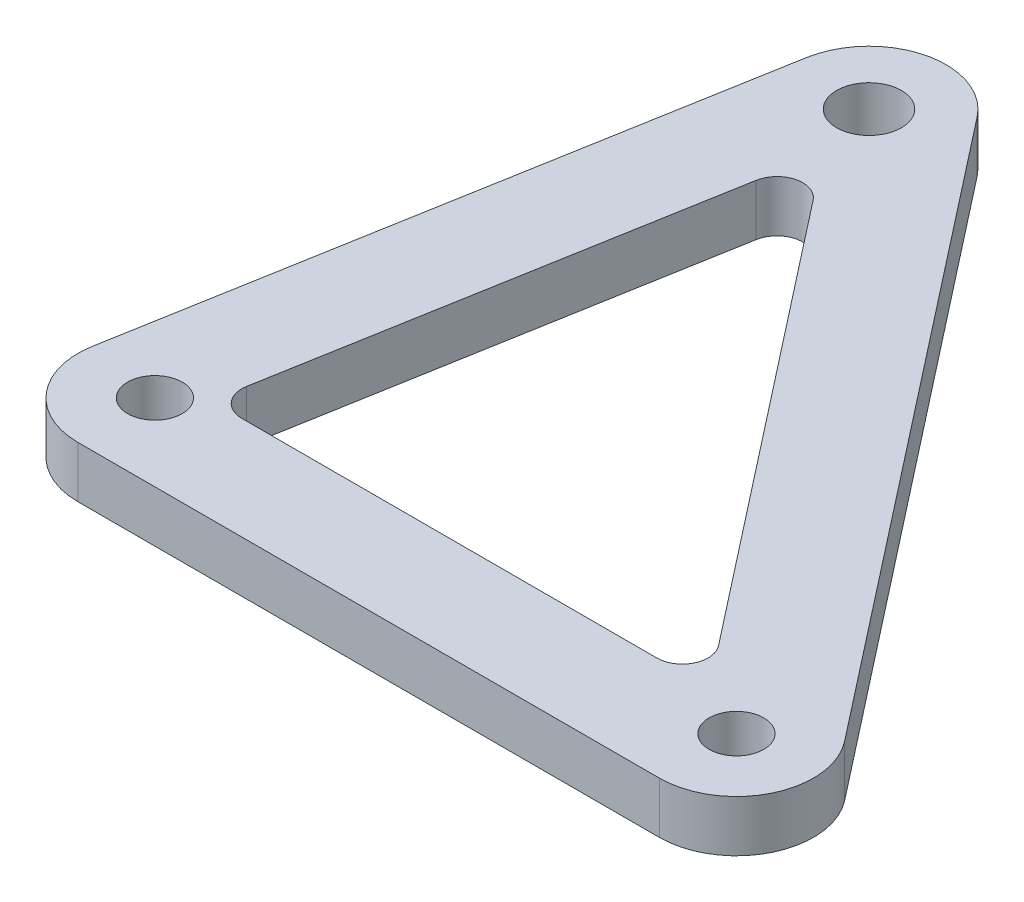
SolidWorks part; units mm, degrees
ref_plane "Front Plane" through (0, 0, 0) normal (0, 0, 1) x (1, 0, 0)
ref_plane "Top Plane" through (0, 0, 0) normal (0, 1, 0) x (1, 0, 0)
ref_plane "Right Plane" through (0, 0, 0) normal (1, 0, 0) x (0, 0, -1)
sketch "Sketch1" plane through (0, 0, 0) normal (0, 1, 0) x (1, 0, 0)
  line L0 (0, 0) -> (71.882, 0) construction
  line L1 (71.882, 0) -> (13.2224, 75.044) construction
  line L2 (13.2224, 75.044) -> (0, 0) construction
  line L3 (6.3163, 90.7407) -> (-10.6935, -5.7991)
  line L4 (-7.5666, -9.525) -> (84.9054, -9.525)
  line L5 (87.4068, -4.3947) -> (11.9446, 92.1451)
  line L6 (19.503, 61.8536) -> (61.3601, 8.3053)
  line L7 (58.8586, 3.175) -> (7.5666, 3.175)
  line L8 (4.4398, 6.9009) -> (13.8747, 60.4492)
  circle A0 centre (0, 0) radius 3.3782
  circle A1 centre (13.2224, 75.044) radius 4
  circle A2 centre (71.882, 0) radius 3.3782
  arc A3 (61.3601, 8.3053) -> (58.8586, 3.175) centre (58.8586, 6.35) cw
  arc A4 (7.5666, 3.175) -> (4.4398, 6.9009) centre (7.5666, 6.35) cw
  arc A5 (19.503, 61.8536) -> (13.8747, 60.4492) centre (17.0016, 59.8983) ccw
  arc A6 (87.4068, -4.3947) -> (84.9054, -9.525) centre (84.9054, -6.35) cw
  arc A7 (-7.5666, -9.525) -> (-10.6935, -5.7991) centre (-7.5666, -6.35) cw
  arc A8 (11.9446, 92.1451) -> (6.3163, 90.7407) centre (9.4431, 90.1898) ccw
  circle A9 centre (71.882, 0) radius 9.525
  circle A10 centre (0, 0) radius 9.525
  circle A11 centre (13.2224, 75.044) radius 9.525
  point P18 (9.1573, 33.6751)
  dimension "D4" = 6.7564
  dimension "D5" = 8
  dimension "D6" = 9.525
  dimension "D12" = 3.175
  dimension "D1" = 71.882
  dimension "D2" = 76.2
  dimension "D3" = 95.25
  dimension "D7" = 9.525
  dimension "D8" = 9.525
  dimension "D9" = 12.7
  dimension "D10" = 12.7
  dimension "D11" = 12.7
extrude "Boss-Extrude2" add sketch "Sketch1" along normal blind 6.35 contours A11 L3 A10 L8 A5 L6 A3 L7 L4 A9 L5 | A10 L7 A4 L8 A0 | A9 A2 | A11 A1
